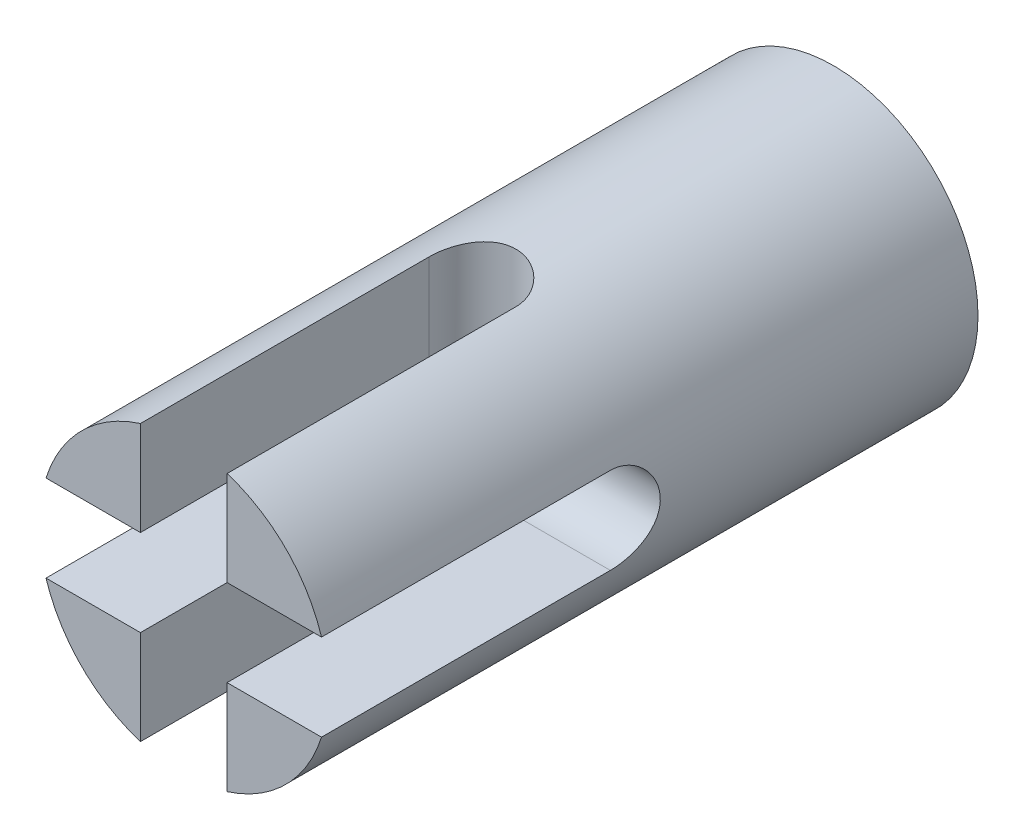
SolidWorks part; units mm, degrees
ref_plane "前视基准面" through (0, 0, 0) normal (0, 0, 1) x (1, 0, 0)
ref_plane "上视基准面" through (0, 0, 0) normal (0, 1, 0) x (1, 0, 0)
ref_plane "右视基准面" through (0, 0, 0) normal (1, 0, 0) x (0, 0, -1)
sketch "草图1" plane through (0, 0, 0) normal (0, 0, 1) x (1, 0, 0)
  circle A0 centre (0, 0) radius 10
  dimension "D1" = 20
extrude "凸台-拉伸1" add sketch "草图1" along normal blind 45
sketch "草图2" plane through (0, 0, 0) normal (0, 1, 0) x (1, 0, 0)
  line L0 (-10, -45) -> (10, -45) construction
  line L2 (3, -45) -> (3, -25)
  line L5 (-3, -45) -> (-3, -25)
  line L6 (0, 0) -> (0, -22) construction
  line L7 (10, 0) -> (-10, 0) construction
  line L8 (-3, -45) -> (3, -45)
  arc A0 (3, -25) -> (-3, -25) centre (0, -25) ccw
  dimension "D3" = 3
  dimension "D1" = 20
  dimension "D2" = 6
extrude "切除-拉伸1" cut sketch "草图2" against normal mid plane 45
sketch "草图4" plane through (0, 0, 45) normal (0, 0, 1) x (1, 0, 0)
  line L1 (14.5318, -3) -> (-14.5318, -3)
  line L2 (14.5318, -3) -> (14.5318, 3)
  line L3 (14.5318, 3) -> (-14.5318, 3)
  line L4 (-14.5318, -3) -> (-14.5318, 3)
  line L5 (14.5318, -3) -> (-14.5318, 3) construction
  line L6 (14.5318, 3) -> (-14.5318, -3) construction
  point P0 (0, 0)
  dimension "D1" = 6
extrude "切除-拉伸2" cut sketch "草图4" against normal blind 20
sketch "草图5" plane through (0, 0, 0) normal (0, 0, -1) x (-1, 0, 0)
  circle A0 centre (0, 0) radius 2.25
  dimension "D1" = 4.5
extrude "切除-拉伸3" cut sketch "草图5" against normal blind 15
ref_plane "基准面1" through (0, 0, 0) normal (-1, 0, 0) x (0, 0, 1)
sketch "草图6" plane through (0, 0, 0) normal (-1, 0, 0) x (0, 0, 1)
  line L0 (25, -3) -> (25, 3) construction
  circle A0 centre (25, 0) radius 3
extrude "切除-拉伸4" cut sketch "草图6" against normal mid plane 46
